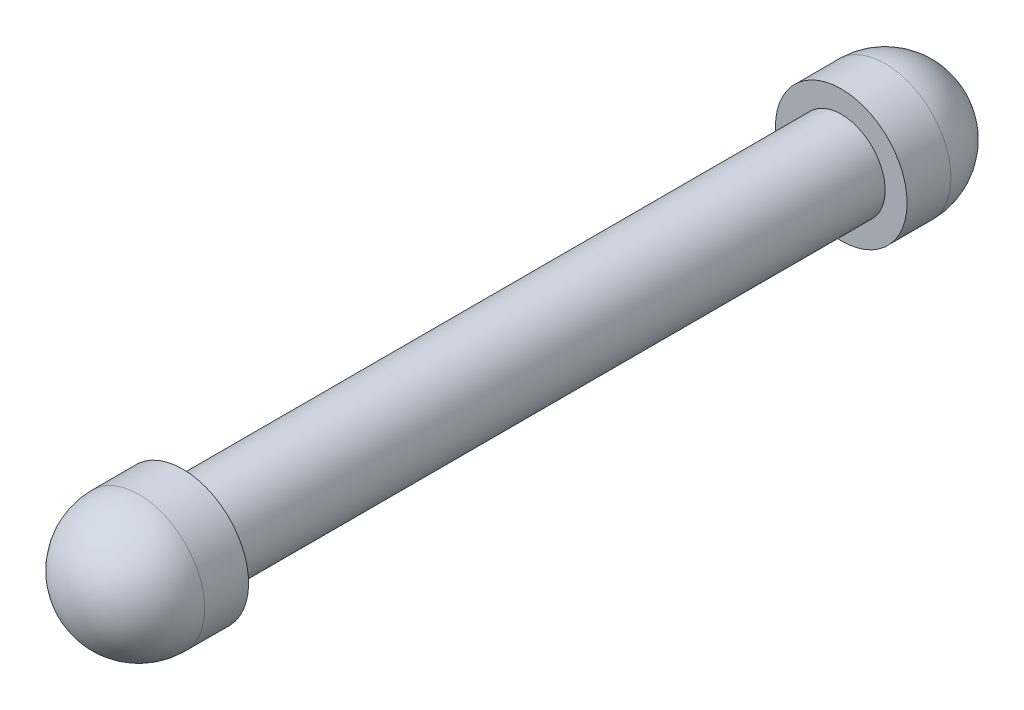
SolidWorks part; units mm, degrees
ref_plane "Front Plane" through (0, 0, 0) normal (0, 0, 1) x (1, 0, 0)
ref_plane "Top Plane" through (0, 0, 0) normal (0, 1, 0) x (1, 0, 0)
ref_plane "Right Plane" through (0, 0, 0) normal (1, 0, 0) x (0, 0, -1)
sketch "Sketch1" plane through (0, 0, 0) normal (1, 0, 0) x (0, 0, -1)
  line L0 (-15, 0) -> (15, 0)
  point P4 (0, 0)
  dimension "D1" = 30
sweep "Sweep1" add path "Sketch1" circular profile diameter 4 parameters "D3"=4
sketch "Sketch11" plane through (0, 0, -15) normal (0, 0, -1) x (-1, 0, 0)
  circle A0 centre (0, 0) radius 3
  dimension "D1" = 6
extrude "Boss-Extrude1" add sketch "Sketch11" along normal blind 5
fillet "Fillet2" radius 3 1 edges at (0, 3, -20)
mirror "Mirror1" about plane through (0, 0, 0) normal (0, 0, 1) of "Boss-Extrude1", "Fillet2"
